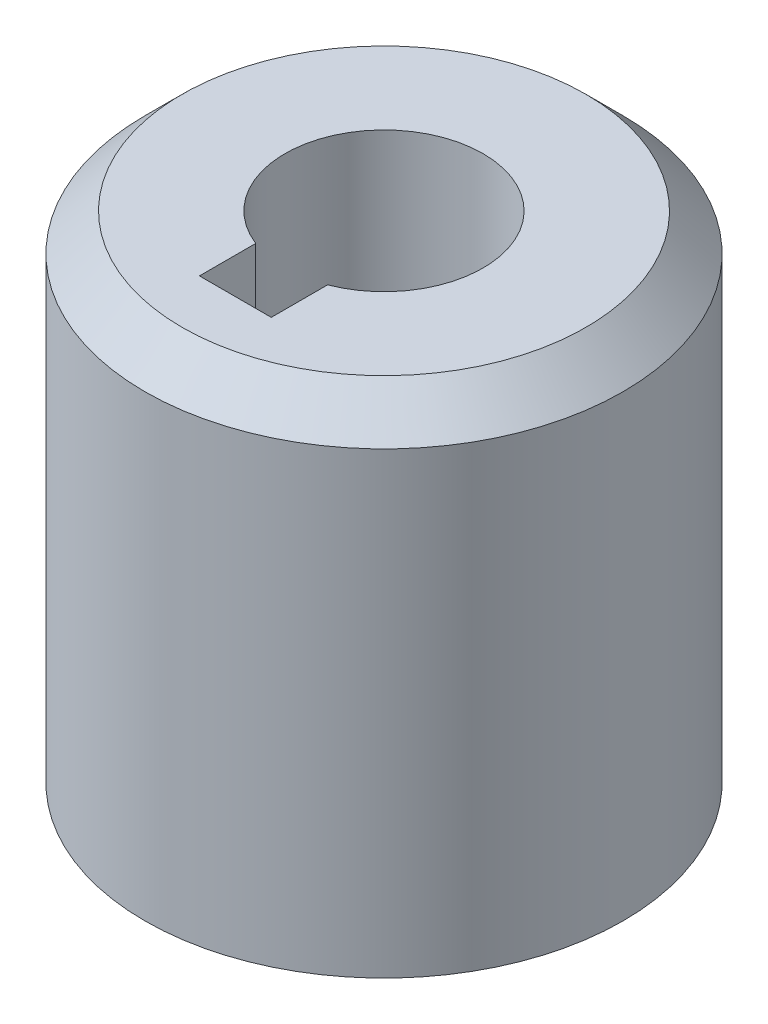
SolidWorks part; units mm, degrees
ref_plane "Front Plane" through (0, 0, 0) normal (0, 0, 1) x (1, 0, 0)
ref_plane "Top Plane" through (0, 0, 0) normal (0, 1, 0) x (1, 0, 0)
ref_plane "Right Plane" through (0, 0, 0) normal (1, 0, 0) x (0, 0, -1)
sketch "Sketch1" plane through (0, 0, 0) normal (0, 1, 0) x (1, 0, 0)
  line L1 (-1.45, -6) -> (1.45, -6)
  line L5 (0, -6) -> (0, -4) construction
  line L8 (-1.45, -6) -> (-1.45, -3.7279)
  line L10 (1.45, -6) -> (1.45, -3.7279)
  circle A0 centre (0, 0) radius 9.65
  arc A1 (1.45, -3.7279) -> (-1.45, -3.7279) centre (0, 0) ccw
  circle A2 centre (0, 0) radius 4 construction
  dimension "D1" = 19.3
  dimension "D2" = 8
  dimension "D3" = 6
  dimension "D4" = 2.9
extrude "Boss-Extrude1" add sketch "Sketch1" along normal blind 20
chamfer "Chamfer1" distance 1.5 angle 45 1 edges at (0, 20, 9.65)
